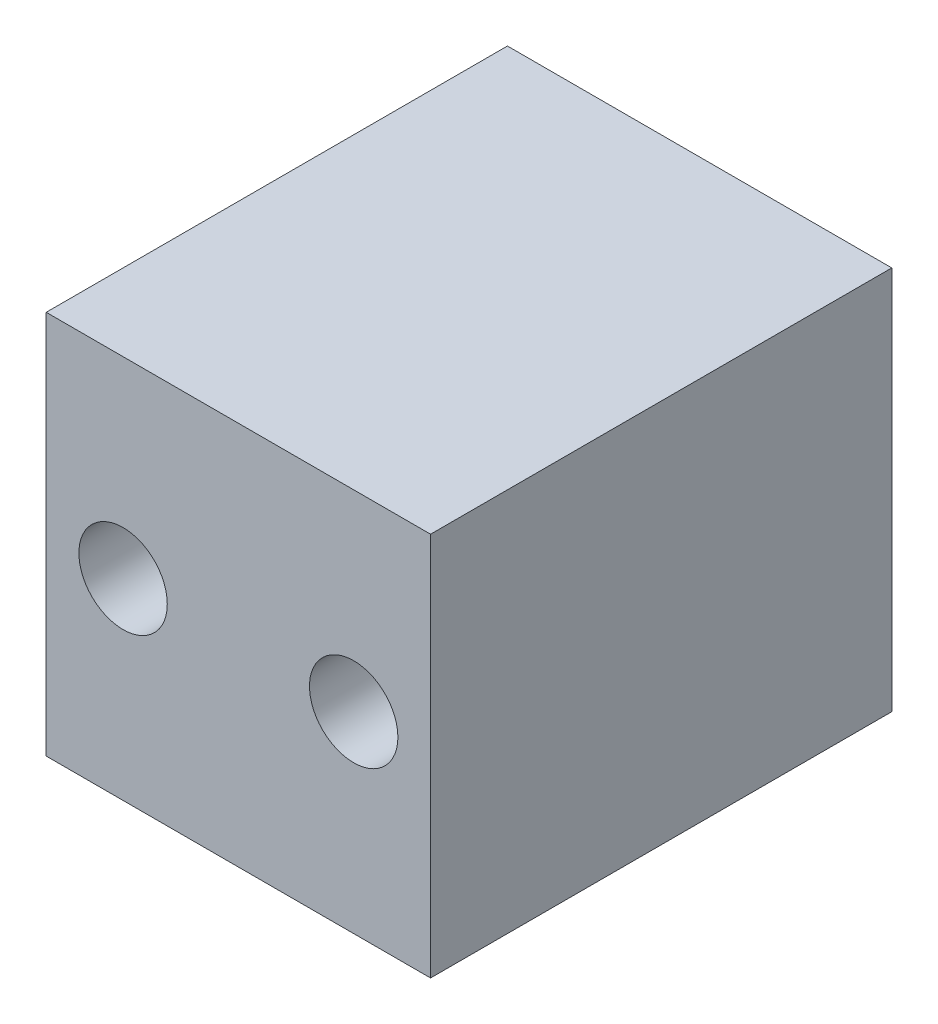
SolidWorks part; units mm, degrees
ref_plane "Ebene vorne" through (0, 0, 0) normal (0, 0, 1) x (1, 0, 0)
ref_plane "Ebene oben" through (0, 0, 0) normal (0, 1, 0) x (1, 0, 0)
ref_plane "Ebene rechts" through (0, 0, 0) normal (1, 0, 0) x (0, 0, -1)
sketch "Skizze1" plane through (0, 0, 0) normal (0, 0, 1) x (1, 0, 0)
  line L1 (50, -50) -> (-50, -50)
  line L2 (50, -50) -> (50, 50)
  line L3 (50, 50) -> (-50, 50)
  line L4 (-50, -50) -> (-50, 50)
  line L5 (50, -50) -> (-50, 50) construction
  line L6 (50, 50) -> (-50, -50) construction
  point P0 (0, 0)
  dimension "D1" = 100
extrude "Aufsatz-Linear austragen1" add sketch "Skizze1" along normal blind 120
hole_wizard "Stirnsenkung für M8 Senkschraube (Kopf Button)1" positions "Skizze3" profile "Skizze2" counterbore size "M8" standard "ANSI Metrisch" end condition through all
sketch "Skizze3" plane through (0, 0, 120) normal (0, 0, 1) x (1, 0, 0)
  line L0 (50, 50) -> (-50, 50) construction
  line L1 (-50, 50) -> (-50, -50) construction
  point P0 (-30, 0)
  point P5 (-50, 0)
  dimension "D1" = 50
  dimension "D2" = 20
sketch "Skizze2" plane through (-30, 0, 120) normal (1, 0, 0) x (0, -1, 0)
  line L0 (0, 0) -> (0, 120)
  line L1 (0, 120) -> (4.5, 120)
  line L3 (4.5, 120) -> (4.5, 110)
  line L4 (4.5, 110) -> (11.5, 110)
  line L5 (11.5, 110) -> (11.5, 0)
  line L7 (11.5, 0) -> (0, 0)
  line L11 (0, -6.35) -> (0, 107.95) construction
  dimension "Bohrerdurchmesser" = 9
  dimension "Bohrungstiefe" = 120
  dimension "Senkdurchmesser2" = 23
  dimension "Senktiefe2" = 110
mirror "Spiegeln1" about plane through (0, 0, 0) normal (1, 0, 0) of "Stirnsenkung für M8 Senkschraube (Kopf Button)1"
